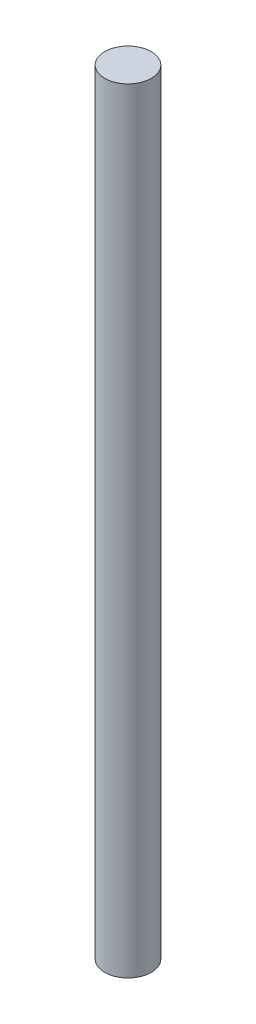
SolidWorks part; units mm, degrees
ref_plane "Front Plane" through (0, 0, 0) normal (0, 0, 1) x (1, 0, 0)
ref_plane "Top Plane" through (0, 0, 0) normal (0, 1, 0) x (1, 0, 0)
ref_plane "Right Plane" through (0, 0, 0) normal (1, 0, 0) x (0, 0, -1)
sketch "Sketch1" plane through (0, 0, 0) normal (0, 1, 0) x (1, 0, 0)
  circle A0 centre (0, 0) radius 6
extrude "Boss-Extrude1" add sketch "Sketch1" along normal blind 200
